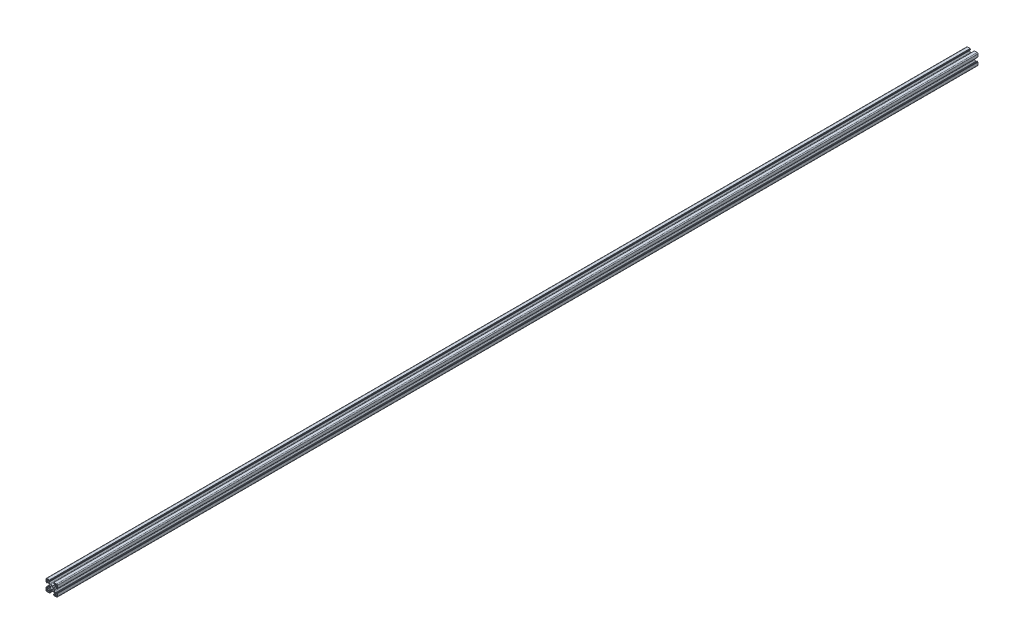
SolidWorks part; units mm, degrees
material "1060 Сплав"
ref_plane "Спереди" through (0, 0, 0) normal (0, 0, 1) x (1, 0, 0)
ref_plane "Сверху" through (0, 0, 0) normal (0, 1, 0) x (1, 0, 0)
ref_plane "Справа" through (0, 0, 0) normal (1, 0, 0) x (0, 0, -1)
sketch "Эскиз1" plane through (0, 0, 0) normal (0, 0, 1) x (1, 0, 0)
  line L0 (9.3595, 9.1357) -> (6.3595, 6.1357) construction
  line L1 (0.2595, 4.0357) -> (2.1582, 4.0357)
  line L2 (0.2595, 0.0357) -> (10.2595, 10.0357) construction
  line L3 (7.8595, 7.6357) -> (6.3595, 9.1357) construction
  line L4 (3.5725, 4.6215) -> (4.8737, 5.9227)
  line L5 (7.1595, 6.1357) -> (8.5595, 6.1357)
  line L6 (6.3595, 6.9357) -> (6.3595, 8.3357)
  line L7 (8.5595, 9.1357) -> (7.1595, 9.1357)
  line L8 (5.4595, 8.2357) -> (5.4595, 7.3369)
  line L9 (4.0227, 8.1089) -> (4.503, 8.5893)
  line L10 (3.4595, 9.5848) -> (3.9595, 9.5848)
  line L11 (3.8459, 8.0357) -> (3.5595, 8.0357)
  line L12 (4.8566, 8.7357) -> (4.9595, 8.7357)
  line L13 (3.9595, 9.8857) -> (3.9595, 9.5848)
  line L14 (3.3095, 9.4348) -> (3.3095, 8.2857)
  line L15 (8.7595, 10.0357) -> (4.1095, 10.0357)
  line L16 (9.3595, 8.3357) -> (9.3595, 6.9357)
  line L17 (10.2595, 8.5357) -> (10.2595, 3.8857)
  line L18 (9.6585, 3.0857) -> (8.5095, 3.0857)
  line L19 (10.1095, 3.7357) -> (9.8085, 3.7357)
  line L20 (8.9595, 4.6328) -> (8.9595, 4.7357)
  line L21 (8.2595, 3.6221) -> (8.2595, 3.3357)
  line L22 (9.8085, 3.2357) -> (9.8085, 3.7357)
  line L23 (8.3327, 3.7989) -> (8.813, 4.2793)
  line L24 (8.4595, 5.2357) -> (7.5607, 5.2357)
  line L25 (4.8452, 3.3487) -> (6.1465, 4.6499)
  line L26 (4.2595, 0.0357) -> (4.2595, 1.9345)
  line L27 (4.2595, 0.0357) -> (4.2595, -1.8631)
  line L28 (4.8452, -3.2773) -> (6.1465, -4.5785)
  line L29 (6.3595, -6.8643) -> (6.3595, -8.2643)
  line L30 (7.1595, -6.0643) -> (8.5595, -6.0643)
  line L31 (9.3595, -8.2643) -> (9.3595, -6.8643)
  line L32 (8.4595, -5.1643) -> (7.5607, -5.1643)
  line L33 (8.3327, -3.7275) -> (8.813, -4.2079)
  line L34 (9.8085, -3.1643) -> (9.8085, -3.6643)
  line L35 (8.2595, -3.5507) -> (8.2595, -3.2643)
  line L36 (8.9595, -4.5614) -> (8.9595, -4.6643)
  line L37 (10.1095, -3.6643) -> (9.8085, -3.6643)
  line L38 (9.6585, -3.0143) -> (8.5095, -3.0143)
  line L39 (10.2595, -8.4643) -> (10.2595, -3.8143)
  line L40 (8.5595, -9.0643) -> (7.1595, -9.0643)
  line L41 (8.7595, -9.9643) -> (4.1095, -9.9643)
  line L42 (3.3095, -9.3634) -> (3.3095, -8.2143)
  line L43 (3.9595, -9.8143) -> (3.9595, -9.5134)
  line L44 (4.8566, -8.6643) -> (4.9595, -8.6643)
  line L45 (3.8459, -7.9643) -> (3.5595, -7.9643)
  line L46 (3.4595, -9.5134) -> (3.9595, -9.5134)
  line L47 (4.0227, -8.0375) -> (4.503, -8.5179)
  line L48 (5.4595, -8.1643) -> (5.4595, -7.2655)
  line L49 (3.5725, -4.5501) -> (4.8737, -5.8513)
  line L50 (0.2595, -3.9643) -> (2.1582, -3.9643)
  line L51 (9.3595, -9.0643) -> (6.3595, -6.0643) construction
  line L52 (0.2595, 0.0357) -> (10.2595, -9.9643) construction
  line L53 (7.8595, -7.5643) -> (9.3595, -6.0643) construction
  line L54 (0.2595, -3.9643) -> (-1.6393, -3.9643)
  line L55 (-3.0535, -4.5501) -> (-4.3548, -5.8513)
  line L56 (-6.6405, -6.0643) -> (-8.0405, -6.0643)
  line L57 (-5.8405, -6.8643) -> (-5.8405, -8.2643)
  line L58 (-8.0405, -9.0643) -> (-6.6405, -9.0643)
  line L59 (-4.9405, -8.1643) -> (-4.9405, -7.2655)
  line L60 (-3.5038, -8.0375) -> (-3.9841, -8.5179)
  line L61 (-2.9405, -9.5134) -> (-3.4405, -9.5134)
  line L62 (-3.327, -7.9643) -> (-3.0405, -7.9643)
  line L63 (-4.3376, -8.6643) -> (-4.4405, -8.6643)
  line L64 (-3.4405, -9.8143) -> (-3.4405, -9.5134)
  line L65 (-2.7905, -9.3634) -> (-2.7905, -8.2143)
  line L66 (-8.2405, -9.9643) -> (-3.5905, -9.9643)
  line L67 (-8.8405, -8.2643) -> (-8.8405, -6.8643)
  line L68 (-9.7405, -8.4643) -> (-9.7405, -3.8143)
  line L69 (-9.1396, -3.0143) -> (-7.9905, -3.0143)
  line L70 (-9.5905, -3.6643) -> (-9.2896, -3.6643)
  line L71 (-8.4405, -4.5614) -> (-8.4405, -4.6643)
  line L72 (-7.7405, -3.5507) -> (-7.7405, -3.2643)
  line L73 (-9.2896, -3.1643) -> (-9.2896, -3.6643)
  line L74 (-7.8138, -3.7275) -> (-8.2941, -4.2079)
  line L75 (-7.9405, -5.1643) -> (-7.0418, -5.1643)
  line L76 (-4.3263, -3.2773) -> (-5.6275, -4.5785)
  line L77 (-3.7405, 0.0357) -> (-3.7405, -1.8631)
  line L78 (-8.8405, -9.0643) -> (-5.8405, -6.0643) construction
  line L79 (0.2595, 0.0357) -> (-9.7405, -9.9643) construction
  line L80 (-7.3405, -7.5643) -> (-5.8405, -9.0643) construction
  line L81 (-3.7405, 0.0357) -> (-3.7405, 1.9345)
  line L82 (-4.3263, 3.3487) -> (-5.6275, 4.6499)
  line L83 (-5.8405, 6.9357) -> (-5.8405, 8.3357)
  line L84 (-6.6405, 6.1357) -> (-8.0405, 6.1357)
  line L85 (-8.8405, 8.3357) -> (-8.8405, 6.9357)
  line L86 (-7.9405, 5.2357) -> (-7.0418, 5.2357)
  line L87 (-7.8138, 3.7989) -> (-8.2941, 4.2793)
  line L88 (-9.2896, 3.2357) -> (-9.2896, 3.7357)
  line L89 (-7.7405, 3.6221) -> (-7.7405, 3.3357)
  line L90 (-8.4405, 4.6328) -> (-8.4405, 4.7357)
  line L91 (-9.5905, 3.7357) -> (-9.2896, 3.7357)
  line L92 (-9.1396, 3.0857) -> (-7.9905, 3.0857)
  line L93 (-9.7405, 8.5357) -> (-9.7405, 3.8857)
  line L94 (-8.0405, 9.1357) -> (-6.6405, 9.1357)
  line L95 (-8.2405, 10.0357) -> (-3.5905, 10.0357)
  line L96 (-2.7905, 9.4348) -> (-2.7905, 8.2857)
  line L97 (-3.4405, 9.8857) -> (-3.4405, 9.5848)
  line L98 (-4.3376, 8.7357) -> (-4.4405, 8.7357)
  line L99 (-3.327, 8.0357) -> (-3.0405, 8.0357)
  line L100 (-2.9405, 9.5848) -> (-3.4405, 9.5848)
  line L101 (-3.5038, 8.1089) -> (-3.9841, 8.5893)
  line L102 (-4.9405, 8.2357) -> (-4.9405, 7.3369)
  line L103 (-3.0535, 4.6215) -> (-4.3548, 5.9227)
  line L104 (0.2595, 4.0357) -> (-1.6393, 4.0357)
  line L105 (-11.5046, 0.0357) -> (11.7638, 0.0357) construction
  line L106 (-8.8405, 9.1357) -> (-5.8405, 6.1357) construction
  line L107 (0.2595, -12.0507) -> (0.2595, 10.7546) construction
  line L108 (0.2595, 0.0357) -> (-9.7405, 10.0357) construction
  line L109 (-7.3405, 7.6357) -> (-8.8405, 6.1357) construction
  arc A0 (9.3595, 8.3357) -> (8.5595, 9.1357) centre (8.5595, 8.3357) ccw
  arc A1 (7.1595, 9.1357) -> (6.3595, 8.3357) centre (7.1595, 8.3357) ccw
  arc A2 (7.1595, 6.1357) -> (6.3595, 6.9357) centre (7.1595, 6.9357) cw
  arc A3 (8.7595, 10.0357) -> (10.2595, 8.5357) centre (8.7595, 8.5357) cw
  arc A4 (3.4595, 9.5848) -> (3.3095, 9.4348) centre (3.4595, 9.4348) ccw
  arc A5 (4.1095, 10.0357) -> (3.9595, 9.8857) centre (4.1095, 9.8857) ccw
  arc A6 (3.8459, 8.0357) -> (4.0227, 8.1089) centre (3.8459, 8.2857) ccw
  arc A7 (3.5595, 8.0357) -> (3.3095, 8.2857) centre (3.5595, 8.2857) cw
  arc A8 (4.503, 8.5893) -> (4.8566, 8.7357) centre (4.8566, 8.2357) cw
  arc A9 (4.9595, 8.7357) -> (5.4595, 8.2357) centre (4.9595, 8.2357) cw
  arc A10 (2.7595, 0.0357) -> (0.2595, 2.5357) centre (0.2595, 0.0357) ccw
  arc A11 (2.1582, 4.0357) -> (3.5725, 4.6215) centre (2.1582, 6.0357) ccw
  arc A12 (5.4595, 7.3369) -> (4.8737, 5.9227) centre (3.4595, 7.3369) cw
  arc A13 (9.3595, 6.9357) -> (8.5595, 6.1357) centre (8.5595, 6.9357) cw
  arc A14 (8.9595, 4.7357) -> (8.4595, 5.2357) centre (8.4595, 4.7357) ccw
  arc A15 (8.813, 4.2793) -> (8.9595, 4.6328) centre (8.4595, 4.6328) ccw
  arc A16 (8.2595, 3.3357) -> (8.5095, 3.0857) centre (8.5095, 3.3357) ccw
  arc A17 (8.2595, 3.6221) -> (8.3327, 3.7989) centre (8.5095, 3.6221) cw
  arc A18 (10.2595, 3.8857) -> (10.1095, 3.7357) centre (10.1095, 3.8857) cw
  arc A19 (9.8085, 3.2357) -> (9.6585, 3.0857) centre (9.6585, 3.2357) cw
  arc A20 (7.5607, 5.2357) -> (6.1465, 4.6499) centre (7.5607, 3.2357) ccw
  arc A21 (4.2595, 1.9345) -> (4.8452, 3.3487) centre (6.2595, 1.9345) cw
  arc A22 (8.5595, -9.0643) -> (9.3595, -8.2643) centre (8.5595, -8.2643) ccw
  arc A23 (9.3595, -6.8643) -> (8.5595, -6.0643) centre (8.5595, -6.8643) ccw
  arc A24 (6.3595, -6.8643) -> (7.1595, -6.0643) centre (7.1595, -6.8643) cw
  arc A25 (10.2595, -8.4643) -> (8.7595, -9.9643) centre (8.7595, -8.4643) cw
  arc A26 (9.8085, -3.1643) -> (9.6585, -3.0143) centre (9.6585, -3.1643) ccw
  arc A27 (10.2595, -3.8143) -> (10.1095, -3.6643) centre (10.1095, -3.8143) ccw
  arc A28 (8.2595, -3.5507) -> (8.3327, -3.7275) centre (8.5095, -3.5507) ccw
  arc A29 (8.2595, -3.2643) -> (8.5095, -3.0143) centre (8.5095, -3.2643) cw
  arc A30 (8.813, -4.2079) -> (8.9595, -4.5614) centre (8.4595, -4.5614) cw
  arc A31 (8.9595, -4.6643) -> (8.4595, -5.1643) centre (8.4595, -4.6643) cw
  arc A32 (0.2595, -2.4643) -> (2.7595, 0.0357) centre (0.2595, 0.0357) ccw
  arc A33 (4.2595, -1.8631) -> (4.8452, -3.2773) centre (6.2595, -1.8631) ccw
  arc A34 (7.5607, -5.1643) -> (6.1465, -4.5785) centre (7.5607, -3.1643) cw
  arc A35 (7.1595, -9.0643) -> (6.3595, -8.2643) centre (7.1595, -8.2643) cw
  arc A36 (4.9595, -8.6643) -> (5.4595, -8.1643) centre (4.9595, -8.1643) ccw
  arc A37 (4.503, -8.5179) -> (4.8566, -8.6643) centre (4.8566, -8.1643) ccw
  arc A38 (3.5595, -7.9643) -> (3.3095, -8.2143) centre (3.5595, -8.2143) ccw
  arc A39 (3.8459, -7.9643) -> (4.0227, -8.0375) centre (3.8459, -8.2143) cw
  arc A40 (4.1095, -9.9643) -> (3.9595, -9.8143) centre (4.1095, -9.8143) cw
  arc A41 (3.4595, -9.5134) -> (3.3095, -9.3634) centre (3.4595, -9.3634) cw
  arc A42 (5.4595, -7.2655) -> (4.8737, -5.8513) centre (3.4595, -7.2655) ccw
  arc A43 (2.1582, -3.9643) -> (3.5725, -4.5501) centre (2.1582, -5.9643) cw
  arc A44 (-8.8405, -8.2643) -> (-8.0405, -9.0643) centre (-8.0405, -8.2643) ccw
  arc A45 (-6.6405, -9.0643) -> (-5.8405, -8.2643) centre (-6.6405, -8.2643) ccw
  arc A46 (-6.6405, -6.0643) -> (-5.8405, -6.8643) centre (-6.6405, -6.8643) cw
  arc A47 (-8.2405, -9.9643) -> (-9.7405, -8.4643) centre (-8.2405, -8.4643) cw
  arc A48 (-2.9405, -9.5134) -> (-2.7905, -9.3634) centre (-2.9405, -9.3634) ccw
  arc A49 (-3.5905, -9.9643) -> (-3.4405, -9.8143) centre (-3.5905, -9.8143) ccw
  arc A50 (-3.327, -7.9643) -> (-3.5038, -8.0375) centre (-3.327, -8.2143) ccw
  arc A51 (-3.0405, -7.9643) -> (-2.7905, -8.2143) centre (-3.0405, -8.2143) cw
  arc A52 (-3.9841, -8.5179) -> (-4.3376, -8.6643) centre (-4.3376, -8.1643) cw
  arc A53 (-4.4405, -8.6643) -> (-4.9405, -8.1643) centre (-4.4405, -8.1643) cw
  arc A54 (-2.2405, 0.0357) -> (0.2595, -2.4643) centre (0.2595, 0.0357) ccw
  arc A55 (-1.6393, -3.9643) -> (-3.0535, -4.5501) centre (-1.6393, -5.9643) ccw
  arc A56 (-4.9405, -7.2655) -> (-4.3548, -5.8513) centre (-2.9405, -7.2655) cw
  arc A57 (-8.8405, -6.8643) -> (-8.0405, -6.0643) centre (-8.0405, -6.8643) cw
  arc A58 (-8.4405, -4.6643) -> (-7.9405, -5.1643) centre (-7.9405, -4.6643) ccw
  arc A59 (-8.2941, -4.2079) -> (-8.4405, -4.5614) centre (-7.9405, -4.5614) ccw
  arc A60 (-7.7405, -3.2643) -> (-7.9905, -3.0143) centre (-7.9905, -3.2643) ccw
  arc A61 (-7.7405, -3.5507) -> (-7.8138, -3.7275) centre (-7.9905, -3.5507) cw
  arc A62 (-9.7405, -3.8143) -> (-9.5905, -3.6643) centre (-9.5905, -3.8143) cw
  arc A63 (-9.2896, -3.1643) -> (-9.1396, -3.0143) centre (-9.1396, -3.1643) cw
  arc A64 (-7.0418, -5.1643) -> (-5.6275, -4.5785) centre (-7.0418, -3.1643) ccw
  arc A65 (-3.7405, -1.8631) -> (-4.3263, -3.2773) centre (-5.7405, -1.8631) cw
  arc A66 (-8.0405, 9.1357) -> (-8.8405, 8.3357) centre (-8.0405, 8.3357) ccw
  arc A67 (-8.8405, 6.9357) -> (-8.0405, 6.1357) centre (-8.0405, 6.9357) ccw
  arc A68 (-5.8405, 6.9357) -> (-6.6405, 6.1357) centre (-6.6405, 6.9357) cw
  arc A69 (-9.7405, 8.5357) -> (-8.2405, 10.0357) centre (-8.2405, 8.5357) cw
  arc A70 (-9.2896, 3.2357) -> (-9.1396, 3.0857) centre (-9.1396, 3.2357) ccw
  arc A71 (-9.7405, 3.8857) -> (-9.5905, 3.7357) centre (-9.5905, 3.8857) ccw
  arc A72 (-7.7405, 3.6221) -> (-7.8138, 3.7989) centre (-7.9905, 3.6221) ccw
  arc A73 (-7.7405, 3.3357) -> (-7.9905, 3.0857) centre (-7.9905, 3.3357) cw
  arc A74 (-8.2941, 4.2793) -> (-8.4405, 4.6328) centre (-7.9405, 4.6328) cw
  arc A75 (-8.4405, 4.7357) -> (-7.9405, 5.2357) centre (-7.9405, 4.7357) cw
  arc A76 (0.2595, 2.5357) -> (-2.2405, 0.0357) centre (0.2595, 0.0357) ccw
  arc A77 (-3.7405, 1.9345) -> (-4.3263, 3.3487) centre (-5.7405, 1.9345) ccw
  arc A78 (-7.0418, 5.2357) -> (-5.6275, 4.6499) centre (-7.0418, 3.2357) cw
  arc A79 (-6.6405, 9.1357) -> (-5.8405, 8.3357) centre (-6.6405, 8.3357) cw
  arc A80 (-4.4405, 8.7357) -> (-4.9405, 8.2357) centre (-4.4405, 8.2357) ccw
  arc A81 (-3.9841, 8.5893) -> (-4.3376, 8.7357) centre (-4.3376, 8.2357) ccw
  arc A82 (-3.0405, 8.0357) -> (-2.7905, 8.2857) centre (-3.0405, 8.2857) ccw
  arc A83 (-3.327, 8.0357) -> (-3.5038, 8.1089) centre (-3.327, 8.2857) cw
  arc A84 (-3.5905, 10.0357) -> (-3.4405, 9.8857) centre (-3.5905, 9.8857) cw
  arc A85 (-2.9405, 9.5848) -> (-2.7905, 9.4348) centre (-2.9405, 9.4348) cw
  arc A86 (-4.9405, 7.3369) -> (-4.3548, 5.9227) centre (-2.9405, 7.3369) ccw
  arc A87 (-1.6393, 4.0357) -> (-3.0535, 4.6215) centre (-1.6393, 6.0357) cw
  point P0 (0.2595, 0.0357)
  point P9 (0.2595, 0.0357)
  point P40 (8.9595, 3.7357)
  point P93 (3.9595, -8.6643)
  point P144 (3.9595, 8.7357)
  point P152 (8.9595, -3.6643)
  point P153 (0.2595, -3.8886)
  point P154 (0.2595, 0.0357)
  point P189 (-8.4405, -3.6643)
  point P228 (-3.4405, -8.6643)
  point P229 (-3.6648, 0.0357)
  point P230 (0.2595, 0.0357)
  point P268 (-3.4405, 8.7357)
  point P273 (4.1837, 0.0357)
  point P306 (-8.4405, 3.7357)
  point P307 (0.2595, 3.96)
  point P309 (0.2595, 0.0357)
  dimension "D3" = 5
  dimension "D6" = 2
  dimension "D1" = 2
  dimension "D2" = 6
  dimension "D4" = 4
  dimension "D5" = 0.9
extrude "Бобышка-Вытянуть1" add sketch "Эскиз1" along normal blind 1620
